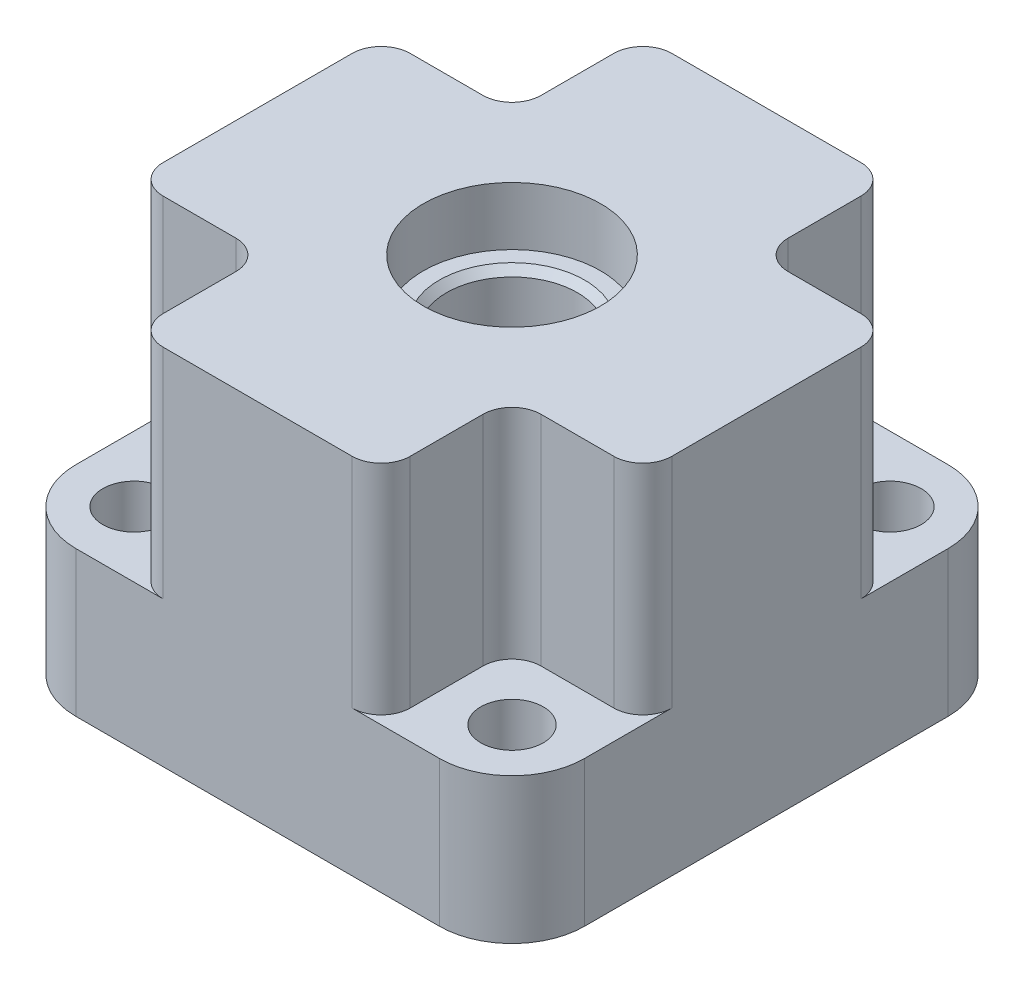
SolidWorks part; units mm, degrees
ref_plane "前视基准面" through (0, 0, 0) normal (0, 0, 1) x (1, 0, 0)
ref_plane "上视基准面" through (0, 0, 0) normal (0, 1, 0) x (1, 0, 0)
ref_plane "右视基准面" through (0, 0, 0) normal (1, 0, 0) x (0, 0, -1)
sketch "草图1" plane through (0, 0, 0) normal (0, 1, 0) x (1, 0, 0)
  line L1 (-17.5, -17.5) -> (17.5, -17.5)
  line L2 (-17.5, -17.5) -> (-17.5, 17.5)
  line L3 (-17.5, 17.5) -> (17.5, 17.5)
  line L4 (17.5, -17.5) -> (17.5, 17.5)
  line L5 (-17.5, -17.5) -> (17.5, 17.5) construction
  line L6 (-17.5, 17.5) -> (17.5, -17.5) construction
  line L7 (-13, -13) -> (13, -13) construction
  line L8 (-13, -13) -> (-13, 13) construction
  line L9 (-13, 13) -> (13, 13) construction
  line L10 (13, -13) -> (13, 13) construction
  line L11 (-13, -13) -> (13, 13) construction
  line L12 (-13, 13) -> (13, -13) construction
  circle A0 centre (0, 0) radius 4.5
  circle A1 centre (13, 13) radius 2.15
  circle A2 centre (13, -13) radius 2.15
  circle A3 centre (-13, -13) radius 2.15
  circle A4 centre (-13, 13) radius 2.15
  circle A5 centre (13, 13) radius 4 construction
  point P0 (0, 0)
  point P22 (0, 0)
  dimension "D1" = 9
  dimension "D6" = 4.3
  dimension "D7" = 4
  dimension "D8" = 8
  dimension "D2" = 35
  dimension "D3" = 35
  dimension "D4" = 26
  dimension "D5" = 26
extrude "凸台-拉伸1" add sketch "草图1" along normal blind 25
fillet "圆角1" radius 5 4 edges at (17.5, 12.5, -17.5) (17.5, 12.5, 17.5) (-17.5, 12.5, 17.5) (-17.5, 12.5, -17.5)
sketch "草图2" plane through (0, 25, 0) normal (0, 1, 0) x (1, 0, 0)
  circle A0 centre (0, 0) radius 6.1 construction
  circle A1 centre (-13, 13) radius 4 construction
  circle A2 centre (0, 0) radius 6.8 construction
  dimension "D1" = 12.2
  dimension "D2" = 8
  dimension "D3" = 13.6
sketch "草图3" plane through (0, 25, 0) normal (0, 1, 0) x (1, 0, 0)
  circle A0 centre (0, 0) radius 6.1 construction
  circle A1 centre (0, 0) radius 6.1
extrude "切除-拉伸1" cut sketch "草图3" against normal blind 4
ref_plane "基准面1" through (0, 13, 0) normal (0, 1, 0) x (1, 0, 0)
sketch "草图4" plane through (0, 13, 0) normal (0, 1, 0) x (1, 0, 0)
  circle A0 centre (0, 0) radius 6.1
  dimension "D1" = 12.2
extrude "切除-拉伸2" cut sketch "草图4" against normal blind 4
sketch "草图6" plane through (0, 0, 0) normal (0, -1, 0) x (1, 0, 0)
  circle A0 centre (0, 0) radius 10
  dimension "D1" = 20
extrude "切除-拉伸3" cut sketch "草图6" against normal blind 9
sketch "草图7" plane through (0, 25, 0) normal (0, 1, 0) x (1, 0, 0)
  line L0 (12.5, 17.5) -> (-12.5, 17.5) construction
  line L1 (-17.5, 8.5) -> (-8.5, 8.5)
  line L2 (-17.5, 8.5) -> (-17.5, 17.5)
  line L3 (-17.5, 17.5) -> (-8.5, 17.5)
  line L4 (-8.5, 8.5) -> (-8.5, 17.5)
  line L5 (-17.5, 8.5) -> (-8.5, 17.5) construction
  line L6 (-17.5, 17.5) -> (-8.5, 8.5) construction
  line L7 (-17.5, 12.5) -> (-17.5, -12.5) construction
  line L8 (8.5, 17.5) -> (17.5, 17.5)
  line L9 (8.5, 17.5) -> (8.5, 8.5)
  line L10 (8.5, 8.5) -> (17.5, 8.5)
  line L11 (17.5, 17.5) -> (17.5, 8.5)
  line L12 (17.5, -8.5) -> (17.5, -17.5)
  line L13 (17.5, -8.5) -> (8.5, -8.5)
  line L14 (8.5, -8.5) -> (8.5, -17.5)
  line L15 (17.5, -17.5) -> (8.5, -17.5)
  line L16 (-8.5, -17.5) -> (-17.5, -17.5)
  line L17 (-8.5, -17.5) -> (-8.5, -8.5)
  line L18 (-8.5, -8.5) -> (-17.5, -8.5)
  line L19 (-17.5, -17.5) -> (-17.5, -8.5)
  point P0 (-13, 13)
  point P25 (0, 0)
  dimension "D1" = 4
extrude "切除-拉伸4" cut sketch "草图7" against normal blind 15
fillet "圆角3" radius 2 12 edges at (17.5, 17.5, -8.5) (8.5, 17.5, -17.5) (8.5, 17.5, -8.5) (17.5, 17.5, 8.5) (8.5, 17.5, 8.5) (8.5, 17.5, 17.5) (-8.5, 17.5, 17.5) (-8.5, 17.5, 8.5) (-17.5, 17.5, 8.5) (-17.5, 17.5, -8.5) (-8.5, 17.5, -8.5) (-8.5, 17.5, -17.5)
chamfer "倒角1" distance 1 angle 45 1 edges at (0, 0, -10)
chamfer "倒角2" distance 0.5 angle 45 2 edges at (0, 13, 4.5) (0, 21, 4.5)
